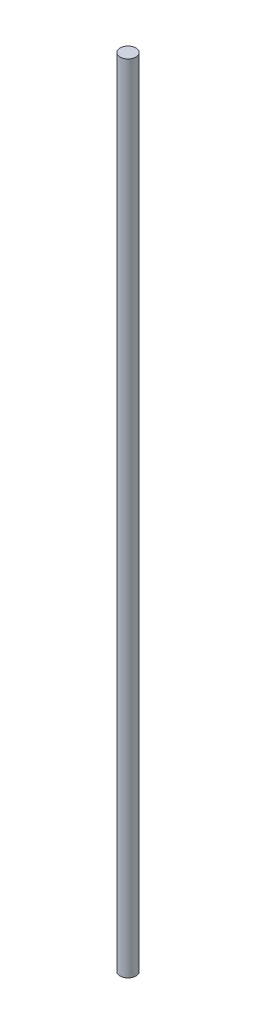
SolidWorks part; units mm, degrees
ref_plane "Plan de face" through (0, 0, 0) normal (0, 0, 1) x (1, 0, 0)
ref_plane "Plan de dessus" through (0, 0, 0) normal (0, 1, 0) x (1, 0, 0)
ref_plane "Plan de droite" through (0, 0, 0) normal (1, 0, 0) x (0, 0, -1)
sketch "Esquisse1" plane through (0, 0, 0) normal (0, 1, 0) x (1, 0, 0)
  circle A0 centre (-18.939, 21.6065) radius 1
  dimension "D1" = 2
extrude "Boss.-Extru.1" add sketch "Esquisse1" along normal blind 100
